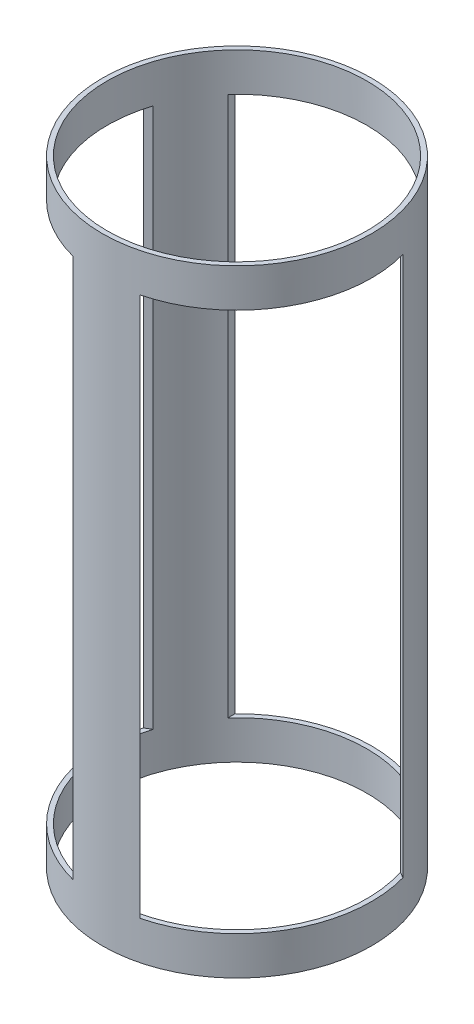
SolidWorks part; units mm, degrees
material "6061-T6 (SS)"
ref_plane "Front Plane" through (0, 0, 0) normal (0, 0, 1) x (1, 0, 0)
ref_plane "Top Plane" through (0, 0, 0) normal (0, 1, 0) x (1, 0, 0)
ref_plane "Right Plane" through (0, 0, 0) normal (1, 0, 0) x (0, 0, -1)
sketch "Sketch1" plane through (0, 0, 0) normal (0, 1, 0) x (1, 0, 0)
  circle A0 centre (0, 0) radius 88.9
  circle A1 centre (0, 0) radius 85.725
  dimension "D1" = 177.8
  dimension "D2" = 171.45
extrude "Boss-Extrude1" add sketch "Sketch1" along normal mid plane 407.162
sketch "Sketch2" plane through (0, 0, 0) normal (0, 0, 1) x (1, 0, 0)
  line L0 (85.725, 203.581) -> (-85.725, 203.581) construction
  line L1 (-63.5, -178.181) -> (63.5, -178.181)
  line L2 (-63.5, -178.181) -> (-63.5, 178.181)
  line L3 (-63.5, 178.181) -> (63.5, 178.181)
  line L4 (63.5, -178.181) -> (63.5, 178.181)
  line L5 (-63.5, -178.181) -> (63.5, 178.181) construction
  line L6 (-63.5, 178.181) -> (63.5, -178.181) construction
  line L7 (88.9, -203.581) -> (88.9, 203.581) construction
  point P0 (0, 0)
  dimension "D1" = 25.4
  dimension "D2" = 25.4
extrude "Cut-Extrude1" cut sketch "Sketch2" against normal up to surface (62.217 mm away)
pattern_circular "CirPattern1" count 3 over 360 about axis through (0, 0, 0) along (0, 1, 0) of "Cut-Extrude1"
ref_plane "Plane1" through (88.9, 0, 0) normal (1, 0, 0) x (0, 0, -1)
sketch "Sketch4" plane through (88.9, 0, 0) normal (1, 0, 0) x (0, 0, -1)
  line L0 (0, 97.79) -> (0, -97.79) construction
  line L1 (88.9, 203.581) -> (-88.9, 203.581) construction
  circle A0 centre (0, 197.231) radius 1.4351
  dimension "D1" = 2.8702
  dimension "D2" = 6.35
extrude "Cut-Extrude3" [suppressed] cut sketch "Sketch4" against normal blind 15.24
pattern_circular "CirPattern3" [suppressed] count 12 over 360
mirror "Mirror1" [suppressed] about plane through (0, 0, 0) normal (0, 1, 0)
ref_plane "Plane2" through (0, 0, 88.9) normal (0, 0, 1) x (1, 0, 0)
sketch "Sketch5" [suppressed] plane through (0, 0, 88.9) normal (0, 0, 1) x (1, 0, 0)
  circle A0 centre (0, -65.7606) radius 1.4351
  circle A1 centre (0, 65.7606) radius 1.4351
  circle A2 centre (0, 197.231) radius 1.4351 construction
  circle A3 centre (0, -197.231) radius 1.4351 construction
  dimension "D1" = 131.4704
  dimension "D2" = 131.4704
  dimension "D3" = 2.8702
  dimension "D4" = 2.8702
extrude "Cut-Extrude4" [suppressed] cut sketch "Sketch5" against normal blind 46.482
pattern_circular "CirPattern4" [suppressed] count 3 over 360
